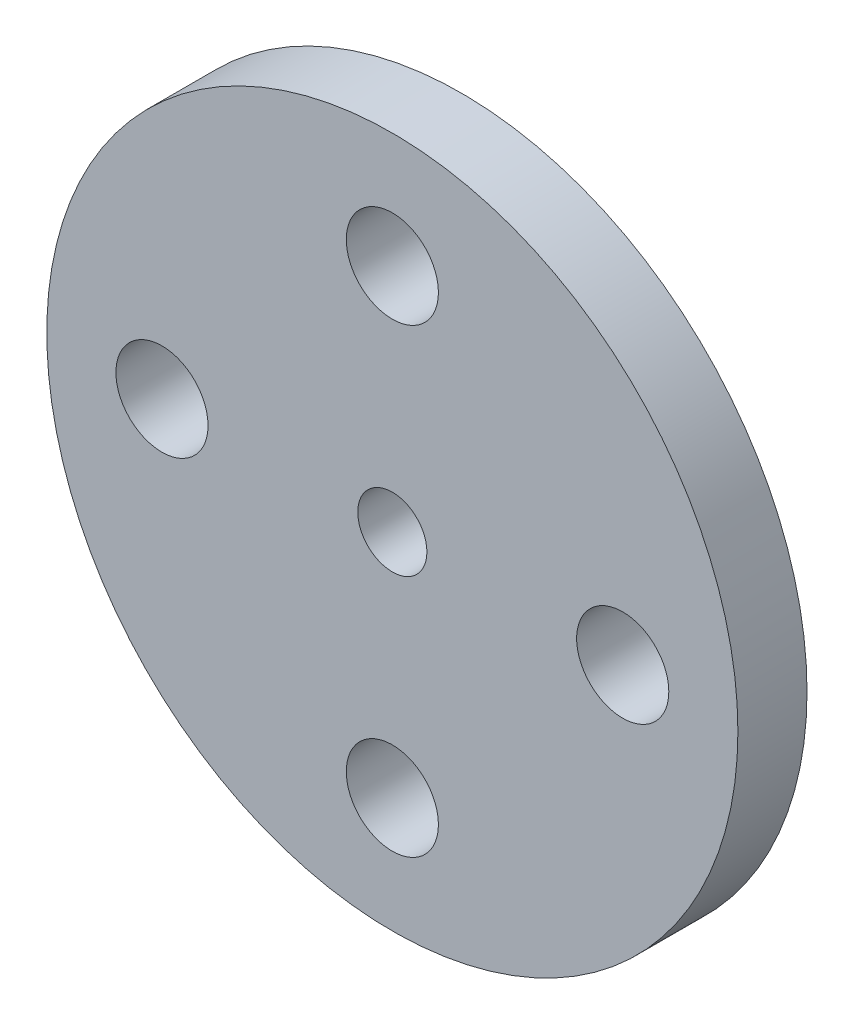
SolidWorks part; units mm, degrees
ref_plane "Front" through (0, 0, 0) normal (0, 0, 1) x (1, 0, 0)
ref_plane "Top" through (0, 0, 0) normal (0, 1, 0) x (1, 0, 0)
ref_plane "Right" through (0, 0, 0) normal (1, 0, 0) x (0, 0, -1)
sketch "草图1" plane through (0, 0, 0) normal (0, 0, 1) x (1, 0, 0)
  circle A0 centre (0, 0) radius 3.5
  circle A1 centre (0, 0) radius 4.5
  dimension "D1" = 7
  dimension "D2" = 9
extrude "凸台-拉伸1" add sketch "草图1" along normal blind 5
sketch "草图2" plane through (0, 0, 5) normal (0, 0, 1) x (1, 0, 0)
  circle A0 centre (0, 0) radius 15
extrude "凸台-拉伸2" add sketch "草图2" along normal blind 3
sketch "草图3" plane through (0, 0, 8) normal (0, 0, 1) x (1, 0, 0)
  line L0 (10, 0) -> (-10, 0) construction
  line L1 (0, -10) -> (0, 10) construction
  circle A0 centre (-10, 0) radius 2
  circle A1 centre (10, 0) radius 2
  circle A2 centre (0, 10) radius 2
  circle A3 centre (0, -10) radius 2
  point P6 (0, 0)
extrude "切除-拉伸1" cut sketch "草图3" against normal blind 3
sketch "草图4" plane through (0, 0, 8) normal (0, 0, 1) x (1, 0, 0)
  circle A0 centre (0, 0) radius 1.5
extrude "切除-拉伸2" cut sketch "草图4" against normal blind 3
